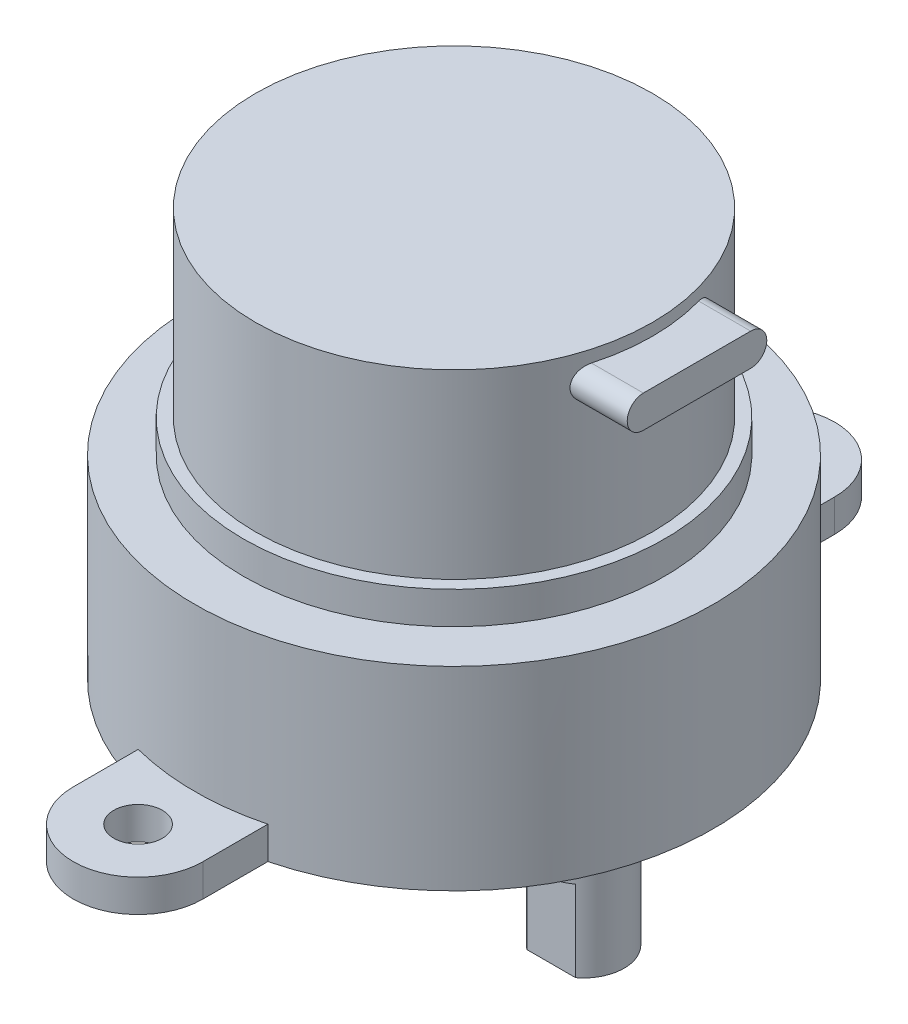
SolidWorks part; units mm, degrees
ref_plane "前视基准面" through (0, 0, 0) normal (0, 0, 1) x (1, 0, 0)
ref_plane "上视基准面" through (0, 0, 0) normal (0, 1, 0) x (1, 0, 0)
ref_plane "右视基准面" through (0, 0, 0) normal (1, 0, 0) x (0, 0, -1)
sketch "草图3" plane through (0, 0, 0) normal (0, 0, 1) x (1, 0, 0)
  line L0 (0, 0) -> (-19.5051, 0) construction
  line L1 (0, -9.2931) -> (0, 15.6319) construction
  line L2 (-16, 0) -> (-16, 12)
  line L3 (-16, 12) -> (-13, 12)
  line L4 (-13, 12) -> (-13, 14)
  line L5 (-13, 14) -> (-12.25, 14)
  line L6 (-12.25, 14) -> (-12.25, 25.2)
  line L7 (-12.25, 25.2) -> (0, 25.2)
  line L8 (0, 0) -> (0, 25.2)
  line L14 (0, 0) -> (-16, 0)
  dimension "D1" = 32
  dimension "D2" = 26
  dimension "D3" = 24.5
  dimension "D4" = 2
  dimension "D5" = 25.2
  dimension "D6" = 12
revolve "旋转1" add sketch "草图3" angle 360 about L8
sketch "草图6" plane through (0, 0, 0) normal (0, 0, 1) x (1, 0, 0)
  line L0 (3.5, 0) -> (3.5, -1.25)
  line L1 (-16, 0) -> (16, 0) construction
  line L2 (3.5, -1.25) -> (4, -1.25)
  line L3 (4, -1.25) -> (4, -2.7)
  line L4 (4, -2.7) -> (5.5, -2.7)
  line L5 (5.5, -2.7) -> (5.5, -10.2)
  line L6 (8, -10.2) -> (5.5, -10.2)
  line L7 (8, -10.2) -> (8, -5.2)
  line L9 (8, 0) -> (8, -13.4458) construction
  line L10 (3.5, 0) -> (8, 0)
  line L11 (8, 0) -> (8, -5.2)
  dimension "D1" = 2.7
  dimension "D2" = 1.25
  dimension "D3" = 5
  dimension "D4" = 8
  dimension "D5" = 10.2
  dimension "D6" = 8
  dimension "D7" = 9
revolve "旋转4" add sketch "草图6" angle 360 about L9
hole_wizard "M3 螺纹孔1" positions "草图7" profile "草图8" tap size "M3" standard "GB"
sketch "草图7" plane through (0, -10.2, 0) normal (0, -1, 0) x (-1, 0, 0)
  point P0 (-8, 0)
cosmetic thread "孔螺蚊线1" parameters "D1"=6, "D2"=3
sketch "草图8" plane through (8, -10.2, 0) normal (1, 0, 0) x (0, 0, -1)
  line L0 (0, 0) -> (0, 8.2511)
  line L1 (0, 8.2511) -> (1.25, 7.5)
  line L2 (1.25, 7.5) -> (1.25, 0)
  line L5 (1.25, 0) -> (0, 0)
  line L10 (0, 8.2511) -> (-1.25, 7.5) construction
  line L11 (0, -6.35) -> (0, 107.95) construction
  dimension "螺纹孔钻头直径" = 2.5
  dimension "螺纹孔钻头深度" = 7.5
  dimension "导头角度" = 118
sketch "草图9" plane through (0, -10.2, 0) normal (0, -1, 0) x (1, 0, 0)
  line L0 (8, 0) -> (16, 0) construction
  line L6 (5.3273, 3.6203) -> (11.0255, 3.6203)
  line L7 (5.3273, 3.6203) -> (5.3273, 2)
  line L8 (5.3273, 2) -> (11.0255, 2)
  line L9 (11.0255, 3.6203) -> (11.0255, 2)
  line L10 (3.6255, -2) -> (11.0255, -2)
  line L11 (3.6255, -2) -> (3.6255, -5.4824)
  line L12 (3.6255, -5.4824) -> (11.0255, -5.4824)
  line L13 (11.0255, -2) -> (11.0255, -5.4824)
  circle A0 centre (0, 0) radius 16 construction
  circle A1 centre (8, 0) radius 4.5 construction
  point P6 (2.5735, 6.0336)
  point P19 (0, 0)
  dimension "D1" = 4
extrude "切除-拉伸1" cut sketch "草图9" against normal blind 5
sketch "草图10" plane through (0, 0, 0) normal (0, -1, 0) x (1, 0, 0)
  line L0 (0, -14.5462) -> (0, 14.7217) construction
  line L1 (0, -19.5) -> (0, 19.5) construction
  line L2 (-4, -19.5) -> (-4, 19.5)
  line L3 (4, -19.5) -> (4, 19.5)
  arc A0 (-4, -19.5) -> (4, -19.5) centre (0, -19.5) ccw
  arc A1 (4, 19.5) -> (-4, 19.5) centre (0, 19.5) ccw
  circle A2 centre (0, 19.5) radius 1.5
  circle A3 centre (0, -19.5) radius 1.5
  point P5 (0, 0)
  dimension "D3" = 3
  dimension "D1" = 8
  dimension "D2" = 39
extrude "凸台-拉伸5" add sketch "草图10" against normal blind 2
sketch "草图11" plane through (0, 0, 0) normal (1, 0, 0) x (0, 0, -1)
  line L0 (0, 25.2) -> (0, 23.4612) construction
  line L1 (12.25, 25.2) -> (-12.25, 25.2) construction
  line L2 (-3.3118, 23.4612) -> (3.3118, 23.4612) construction
  line L3 (-3.3118, 24.4573) -> (3.3118, 24.4573)
  line L4 (-3.3118, 22.4652) -> (3.3118, 22.4652)
  arc A0 (-3.3118, 24.4573) -> (-3.3118, 22.4652) centre (-3.3118, 23.4612) ccw
  arc A1 (3.3118, 22.4652) -> (3.3118, 24.4573) centre (3.3118, 23.4612) ccw
  point P6 (0, 23.4612)
extrude "凸台-拉伸6" add sketch "草图11" along normal blind 15
